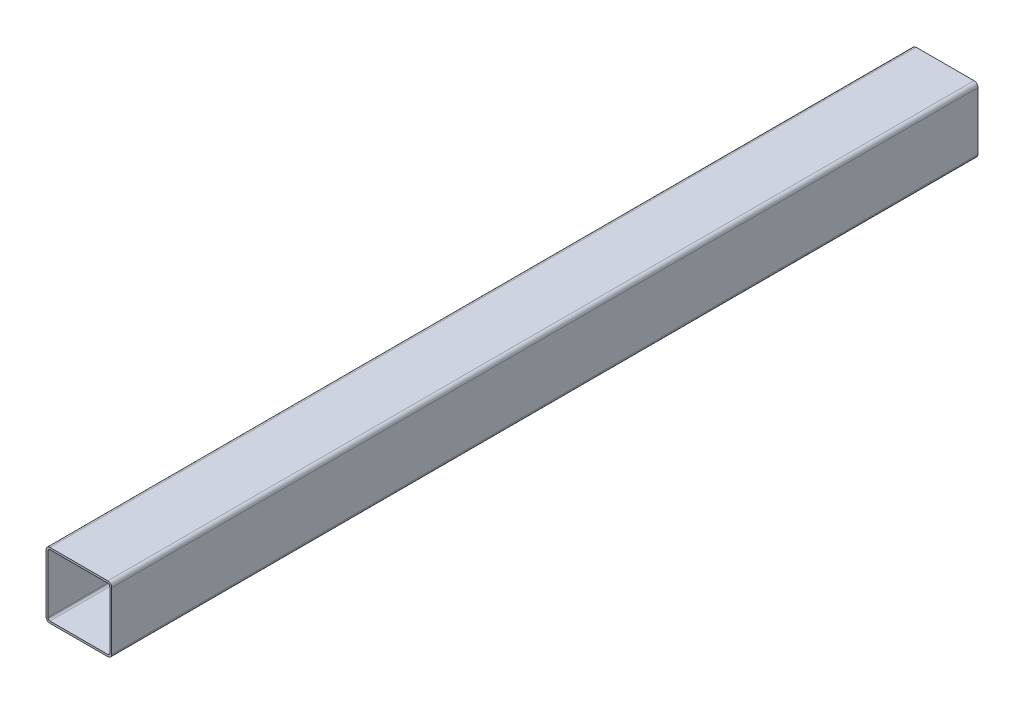
SolidWorks part; units mm, degrees
ref_plane "Front Plane" through (0, 0, 0) normal (0, 0, 1) x (1, 0, 0)
ref_plane "Top Plane" through (0, 0, 0) normal (0, 1, 0) x (1, 0, 0)
ref_plane "Right Plane" through (0, 0, 0) normal (1, 0, 0) x (0, 0, -1)
sketch "Sketch1" plane through (0, 0, 0) normal (0, 0, 1) x (1, 0, 0)
  line L0 (3, 6) -> (3, 94)
  line L1 (6, 0) -> (94, 0)
  line L2 (0, 6) -> (0, 94)
  line L3 (6, 100) -> (94, 100)
  line L4 (100, 6) -> (100, 94)
  line L5 (6, 97) -> (94, 97)
  line L6 (97, 6) -> (97, 94)
  line L7 (6, 3) -> (94, 3)
  arc A0 (94, 0) -> (100, 6) centre (94, 6) ccw
  arc A1 (94, 100) -> (100, 94) centre (94, 94) cw
  arc A2 (0, 94) -> (6, 100) centre (6, 94) cw
  arc A3 (6, 0) -> (0, 6) centre (6, 6) cw
  arc A4 (3, 94) -> (6, 97) centre (6, 94) cw
  arc A5 (94, 97) -> (97, 94) centre (94, 94) cw
  arc A6 (94, 3) -> (97, 6) centre (94, 6) ccw
  arc A7 (6, 3) -> (3, 6) centre (6, 6) cw
  point P7 (100, 0)
  point P12 (0, 100)
  point P15 (0, 0)
  dimension "D3" = 6
  dimension "D1" = 100
  dimension "D2" = 100
  dimension "D4" = 3
extrude "Boss-Extrude1" add sketch "Sketch1" along normal blind 1318
